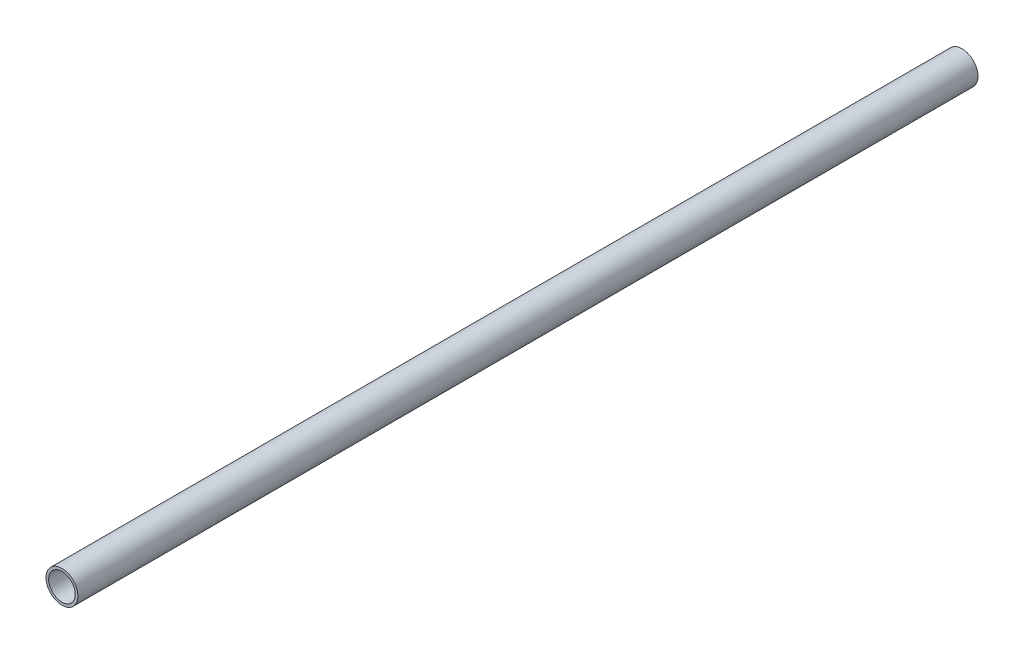
SolidWorks part; units mm, degrees
material "Thornel Mat VMA"
ref_plane "前视基准面" through (0, 0, 0) normal (0, 0, 1) x (1, 0, 0)
ref_plane "上视基准面" through (0, 0, 0) normal (0, 1, 0) x (1, 0, 0)
ref_plane "右视基准面" through (0, 0, 0) normal (1, 0, 0) x (0, 0, -1)
sketch "草图1" plane through (0, 0, 0) normal (0, 0, 1) x (1, 0, 0)
  circle A0 centre (0, 0) radius 5
  circle A1 centre (0, 0) radius 6
extrude "凸台-拉伸1" add sketch "草图1" along normal blind 338
